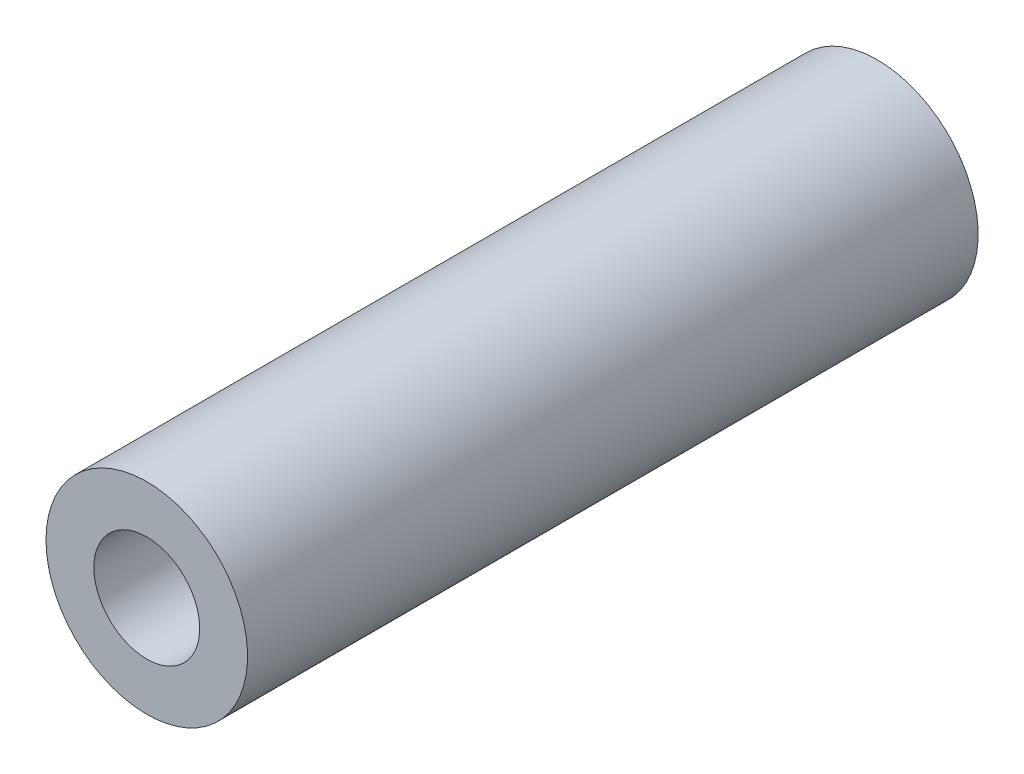
SolidWorks part; units mm, degrees
ref_plane "正面" through (0, 0, 0) normal (0, 0, 1) x (1, 0, 0)
ref_plane "平面" through (0, 0, 0) normal (0, 1, 0) x (1, 0, 0)
ref_plane "右側面" through (0, 0, 0) normal (1, 0, 0) x (0, 0, -1)
sketch "ｽｹｯﾁ1" plane through (0, 0, 0) normal (0, 0, 1) x (1, 0, 0)
  circle A0 centre (0, 0) radius 2.1
  circle A1 centre (0, 0) radius 4
  dimension "D1" = 4.2
  dimension "D2" = 8
extrude "ﾎﾞｽ - 押し出し1" add sketch "ｽｹｯﾁ1" along normal blind 29
